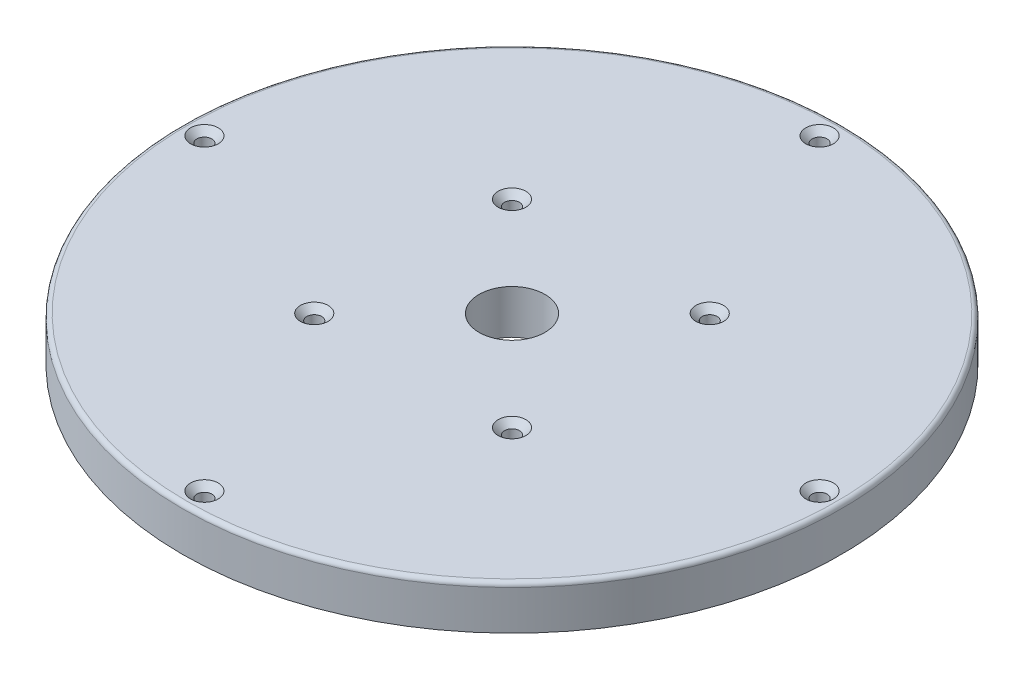
SolidWorks part; units mm, degrees
material "ABS"
ref_plane "Front Plane" through (0, 0, 0) normal (0, 0, 1) x (1, 0, 0)
ref_plane "Top Plane" through (0, 0, 0) normal (0, 1, 0) x (1, 0, 0)
ref_plane "Right Plane" through (0, 0, 0) normal (1, 0, 0) x (0, 0, -1)
sketch "Sketch1" plane through (0, 0, 0) normal (0, 1, 0) x (1, 0, 0)
  circle A0 centre (0, 0) radius 75
  dimension "D1" = 150
extrude "Boss-Extrude1" add sketch "Sketch1" along normal blind 10
sketch "Sketch2" plane through (0, 10, 0) normal (0, 1, 0) x (1, 0, 0)
  line L0 (0, 0) -> (0, 70) construction
  circle A0 centre (0, 0) radius 70
  dimension "D1" = 140
hole_wizard "CSK for M3 Flat Head Machine Screw1" positions "Sketch6" profile "Sketch4" countersink size "M3" standard "ANSI Metric" end condition through all
sketch "Sketch6" plane through (0, 10, 0) normal (0, 1, 0) x (1, 0, 0)
  point P0 (0, 70)
sketch "Sketch4" plane through (0, 10, -70) normal (1, 0, 0) x (0, 0, 1)
  line L0 (0, 0) -> (0, 10)
  line L1 (0, 10) -> (1.7, 10)
  line L2 (1.7, 10) -> (1.7, 1.45)
  line L3 (1.7, 1.45) -> (3.15, 0)
  line L5 (3.15, 0) -> (0, 0)
  line L6 (-1.7, 1.45) -> (-3.15, 0) construction
  line L11 (0, -6.35) -> (0, 107.95) construction
  dimension "Thru Hole Dia." = 3.4
  dimension "Thru Hole Depth" = 10
  dimension "Near C'Sink Dia." = 6.3
  dimension "Near C'Sink Angle" = 90
pattern_circular "CirPattern1" count 4 over 360 about axis through (0, 0, 0) along (0, 1, 0) of "CSK for M3 Flat Head Machine Screw1"
sketch "Sketch8" plane through (0, 10, 0) normal (0, 1, 0) x (1, 0, 0)
  circle A0 centre (0, 0) radius 7.5
  dimension "D1" = 15
extrude "Cut-Extrude1" cut sketch "Sketch8" against normal through all contours A0
sketch "Sketch9" plane through (0, 10, 0) normal (0, 1, 0) x (1, 0, 0)
  line L1 (22.5, 22.5) -> (-22.5, 22.5)
  line L2 (22.5, 22.5) -> (22.5, -22.5)
  line L3 (22.5, -22.5) -> (-22.5, -22.5)
  line L4 (-22.5, 22.5) -> (-22.5, -22.5)
  line L5 (22.5, 22.5) -> (-22.5, -22.5) construction
  line L6 (22.5, -22.5) -> (-22.5, 22.5) construction
  point P0 (0, 0)
  dimension "D1" = 45
  dimension "D2" = 45
hole_wizard "CSK for M3 Flat Head Machine Screw2" positions "Sketch10" profile "Sketch11" countersink size "M3" standard "ANSI Metric" end condition through all
sketch "Sketch10" plane through (0, 10, 0) normal (0, 1, 0) x (1, 0, 0)
  point P0 (22.5, 22.5)
  point P3 (22.5, -22.5)
  point P6 (-22.5, -22.5)
  point P9 (-22.5, 22.5)
sketch "Sketch11" plane through (22.5, 10, -22.5) normal (1, 0, 0) x (0, 0, 1)
  line L0 (0, 0) -> (0, 10)
  line L1 (0, 10) -> (1.7, 10)
  line L2 (1.7, 10) -> (1.7, 1.45)
  line L3 (1.7, 1.45) -> (3.15, 0)
  line L5 (3.15, 0) -> (0, 0)
  line L6 (-1.7, 1.45) -> (-3.15, 0) construction
  line L11 (0, -6.35) -> (0, 107.95) construction
  dimension "Thru Hole Dia." = 3.4
  dimension "Thru Hole Depth" = 10
  dimension "Near C'Sink Dia." = 6.3
  dimension "Near C'Sink Angle" = 90
fillet "Fillet1" radius 1 1 edges at (0, 10, 75)
